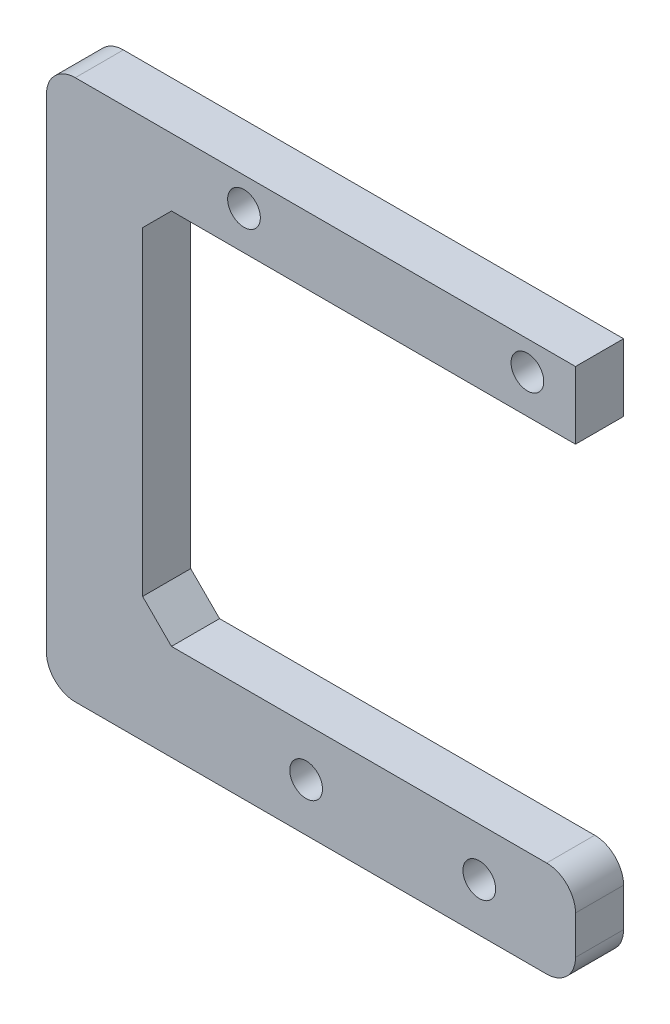
SolidWorks part; units mm, degrees
ref_plane "前视基准面" through (0, 0, 0) normal (0, 0, 1) x (1, 0, 0)
ref_plane "上视基准面" through (0, 0, 0) normal (0, 1, 0) x (1, 0, 0)
ref_plane "右视基准面" through (0, 0, 0) normal (1, 0, 0) x (0, 0, -1)
other "Configuration Table"
sketch "草图1" plane through (0, 0, 0) normal (0, 0, 1) x (1, 0, 0)
  line L0 (0, 0) -> (-55, 0)
  line L1 (-55, 0) -> (-55, 56.2)
  line L2 (-55, 56.2) -> (0, 56.2)
  line L3 (0, 56.2) -> (0, 49.2)
  line L4 (0, 49.2) -> (-45, 49.2)
  line L5 (-45, 49.2) -> (-45, 10)
  line L6 (-45, 10) -> (0, 10)
  line L7 (0, 10) -> (0, 0)
  line L8 (-56.1954, 5) -> (14.7529, 5) construction
  line L9 (-55.2769, 53.2) -> (15.6714, 53.2) construction
  circle A0 centre (-10, 5) radius 1.7
  circle A1 centre (-28, 5) radius 1.7
  circle A2 centre (-5, 53.2) radius 1.7
  circle A3 centre (-34.46, 53.2) radius 1.7
  dimension "D6" = 3.4
  dimension "D7" = 3.4
  dimension "D8" = 3.4
  dimension "D9" = 3.4
  dimension "D1" = 55
  dimension "D2" = 10
  dimension "D3" = 7
  dimension "D4" = 10
  dimension "D5" = 56.2
  dimension "D10" = 3
  dimension "D11" = 18
  dimension "D12" = 10
  dimension "D13" = 5
  dimension "D14" = 29.46
  dimension "D15" = 5
extrude "凸台-拉伸1" add sketch "草图1" along normal blind 5
fillet "圆角1" radius 3 4 edges at (0, 0, 2.5) (0, 10, 2.5) (-55, 56.2, 2.5) (-55, 0, 2.5)
chamfer "倒角1" distance 3 angle 45 2 edges at (-45, 10, 2.5) (-45, 49.2, 2.5)
